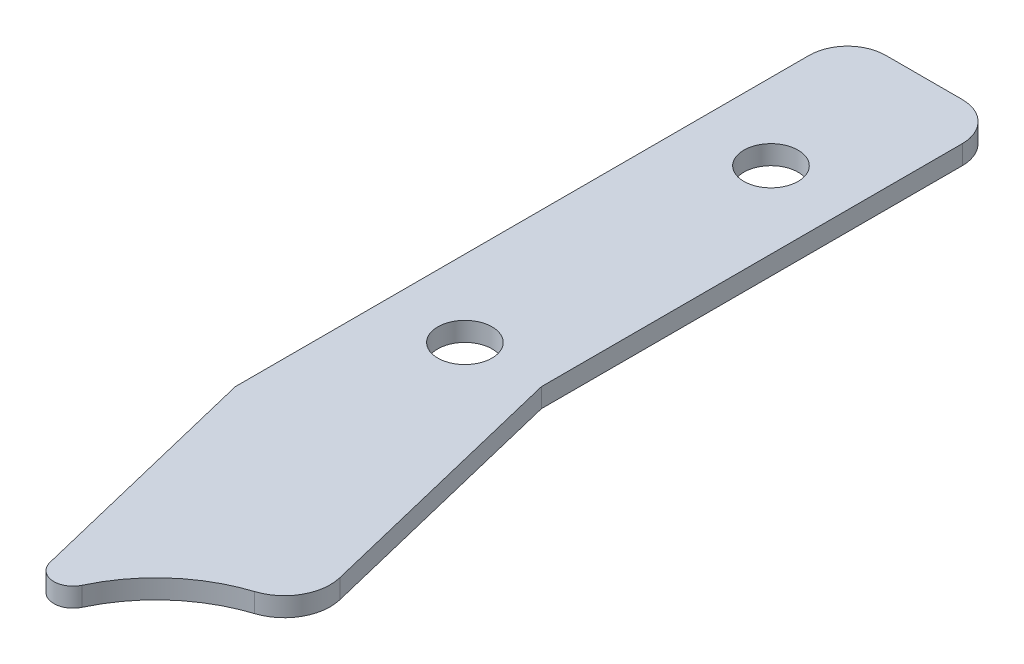
SolidWorks part; units mm, degrees
material "ASTM A36 Steel"
ref_plane "X-Y Datum" through (0, 0, 0) normal (0, 0, 1) x (1, 0, 0)
ref_plane "X-Z Datum" through (0, 0, 0) normal (0, 1, 0) x (1, 0, 0)
ref_plane "Y-Z Datum" through (0, 0, 0) normal (1, 0, 0) x (0, 0, -1)
sketch "Sketch1" plane through (0, 0, 0) normal (0, 1, 0) x (1, 0, 0)
  line L0 (-240.4397, -89.0347) -> (-247.5083, -59.934)
  line L1 (-228.4851, -73.2656) -> (-234.8083, -47.234)
  line L3 (-247.5083, -91.3263) -> (-247.5083, -59.934)
  line L4 (-247.5083, -12.309) -> (-247.5083, -59.934)
  line L5 (-247.5083, -59.934) -> (-234.8083, -59.934)
  line L6 (-234.8083, -59.934) -> (-234.8083, -12.309)
  line L7 (-237.9833, -9.134) -> (-244.3333, -9.134)
  line L8 (-247.5083, -12.309) -> (-247.5083, -59.934)
  line L9 (-247.5083, -59.934) -> (-234.8083, -59.934)
  line L10 (-234.8083, -59.934) -> (-234.8083, -12.309)
  line L11 (-237.9833, -9.134) -> (-244.3333, -9.134)
  arc A4 (-234.8083, -12.309) -> (-237.9833, -9.134) centre (-237.9833, -12.309) ccw
  arc A5 (-234.8083, -12.309) -> (-237.9833, -9.134) centre (-237.9833, -12.309) ccw
  arc A6 (-244.3333, -9.134) -> (-247.5083, -12.309) centre (-244.3333, -12.309) ccw
  arc A7 (-244.3333, -9.134) -> (-247.5083, -12.309) centre (-244.3333, -12.309) ccw
  spline S0 degree 3 poles (-225.8829, -98.6041) (-250.897, -103.0148) (-255.3319, -77.863) (-230.3178, -73.4524) (-205.3037, -69.0417) (-200.8688, -94.1935) (-225.8829, -98.6041) (-250.897, -103.0148) (-255.3319, -77.863) knots -0.5 0 0 0 0.5 0.5 0.5 1 1 1 1.5 1.5 1.5 weights 1 0.333333 0.333333 1 0.333333 0.333333 1 0.333333 0.333333 only from (-225.8829, -98.6041) to (-225.8829, -98.6041)
  spline S1 degree 3 poles (-225.8829, -98.6041) (-250.897, -103.0148) (-255.3319, -77.863) (-230.3178, -73.4524) (-205.3037, -69.0417) (-200.8688, -94.1935) (-225.8829, -98.6041) (-250.897, -103.0148) (-255.3319, -77.863) knots -0.5 0 0 0 0.5 0.5 0.5 1 1 1 1.5 1.5 1.5 weights 1 0.333333 0.333333 1 0.333333 0.333333 1 0.333333 0.333333 only from (-225.8829, -98.6041) to (-225.8829, -98.6041)
  dimension "D2" = 12.7
  dimension "D1" = 0
extrude "Boss-Extrude1" add sketch "Sketch1" along normal blind 1.5875 contours L0 S1 L1 L10 L9 | L10 L11 L8 L9
fillet "Fillet1" radius 3.81 1 edges at (-228.4851, 0.7937, 73.2656)
fillet "Fillet2" radius 1.5875 1 edges at (-240.4397, 0.7937, 89.0347)
sketch "Sketch8" plane through (0, 1.5875, 0) normal (0, 1, 0) x (1, 0, 0)
  circle A0 centre (-241.1583, -21.834) radius 2.25
  circle A1 centre (-241.1583, -47.234) radius 2.25
  dimension "D1" = 4.5
extrude "Cut-Extrude1" cut sketch "Sketch8" against normal blind 3.175
